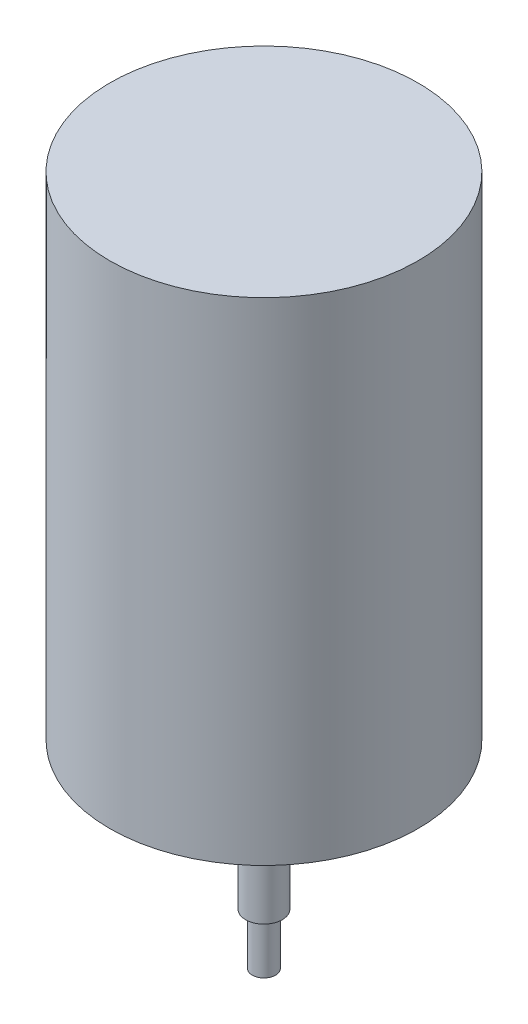
SolidWorks part; units mm, degrees
ref_plane "前视基准面" through (0, 0, 0) normal (0, 0, 1) x (1, 0, 0)
ref_plane "上视基准面" through (0, 0, 0) normal (0, 1, 0) x (1, 0, 0)
ref_plane "右视基准面" through (0, 0, 0) normal (1, 0, 0) x (0, 0, -1)
sketch "草图1" plane through (0, 0, 0) normal (0, 1, 0) x (1, 0, 0)
  circle A0 centre (0, 0) radius 21
  dimension "D1" = 42
extrude "凸台-拉伸1" add sketch "草图1" along normal blind 67
sketch "草图2" plane through (0, 0, 0) normal (0, -1, 0) x (1, 0, 0)
  circle A0 centre (0, 0) radius 2.5
  dimension "D1" = 5
extrude "凸台-拉伸2" add sketch "草图2" along normal blind 20
sketch "草图3" plane through (0, -20, 0) normal (0, -1, 0) x (1, 0, 0)
  circle A0 centre (0, 0) radius 1.5875
  dimension "D1" = 3.175
extrude "凸台-拉伸3" add sketch "草图3" along normal blind 7
